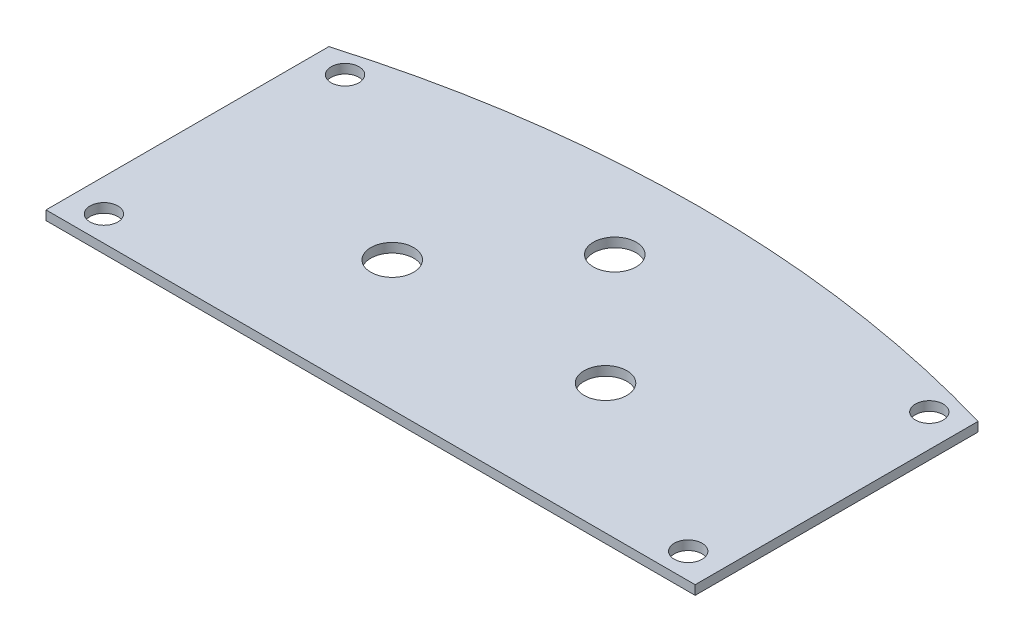
SolidWorks part; units mm, degrees
ref_plane "Front Plane" through (0, 0, 0) normal (0, 0, 1) x (1, 0, 0)
ref_plane "Top Plane" through (0, 0, 0) normal (0, 1, 0) x (1, 0, 0)
ref_plane "Right Plane" through (0, 0, 0) normal (1, 0, 0) x (0, 0, -1)
sketch "Sketch1" plane through (0, 0, 0) normal (0, 1, 0) x (1, 0, 0)
  line L1 (70, 28.5) -> (70, -32.5)
  line L3 (-70, -32.5) -> (-70, 28.5)
  line L4 (-70, -32.5) -> (70, -32.5)
  arc A0 (-70, 28.5) -> (70, 28.5) centre (0, -210.1566) cw
  dimension "D1" = 61
  dimension "D2" = 140
  dimension "D3" = 61
  dimension "D4" = 70
extrude "Boss-Extrude1" add sketch "Sketch1" along normal blind 3
sketch "Sketch3" plane through (0, 3, 0) normal (0, 1, 0) x (1, 0, 0)
  line L0 (0, 43.0385) -> (0, -46.4553) construction
  line L1 (-70, -32.5) -> (70, -32.5) construction
  circle A13 centre (-63, 25) radius 3
  circle A14 centre (-63, -27) radius 3
  circle A15 centre (63, 25) radius 3
  circle A16 centre (63, -27) radius 3
  dimension "D3" = 5.5
  dimension "D13" = 89.4937
  dimension "D15" = 52
  dimension "D16" = 52
  dimension "D2" = 5.5
extrude "Cut-Extrude1" cut sketch "Sketch3" against normal blind 10
sketch "Sketch4" plane through (0, 3, 0) normal (0, 1, 0) x (1, 0, 0)
  line L0 (-70, 28.5) -> (-70, -32.5) construction
  line L1 (-70, -32.5) -> (70, -32.5) construction
  circle A0 centre (-23.33, -4.5) radius 4.62
  circle A1 centre (22.67, -4.5) radius 4.62
  circle A2 centre (-0.33, 20.4992) radius 4.62
  dimension "D1" = 9.24
  dimension "D3" = 28
  dimension "D4" = 46
  dimension "D5" = 33.97
  dimension "D6" = 33.97
  dimension "D2" = 46.67
extrude "Cut-Extrude2" cut sketch "Sketch4" against normal blind 10
sketch "Sketch5" plane through (0, 0, 32.5) normal (0, 0, 1) x (1, 0, 0)
  line L0 (70, 3) -> (70, 0) construction
  line L1 (-70, 0) -> (70, 0)
  line L2 (-70, 0) -> (-70, 1)
  line L3 (-70, 1) -> (70, 1)
  line L4 (70, 0) -> (70, 1)
  dimension "D1" = 1
extrude "Cut-Extrude3" cut sketch "Sketch5" against normal blind 80
sketch "Sketch6" plane through (0, 0, 32.5) normal (0, 0, 1) x (1, 0, 0)
  line L0 (0, 1) -> (0, 3)
  line L1 (70, 1) -> (-70, 1) construction
  line L2 (-70, 3) -> (70, 3) construction
  line L3 (-37.155, 3) -> (-37.155, 1)
  line L4 (24.8759, 3) -> (24.8759, 1)
  dimension "D1" = 37.155
